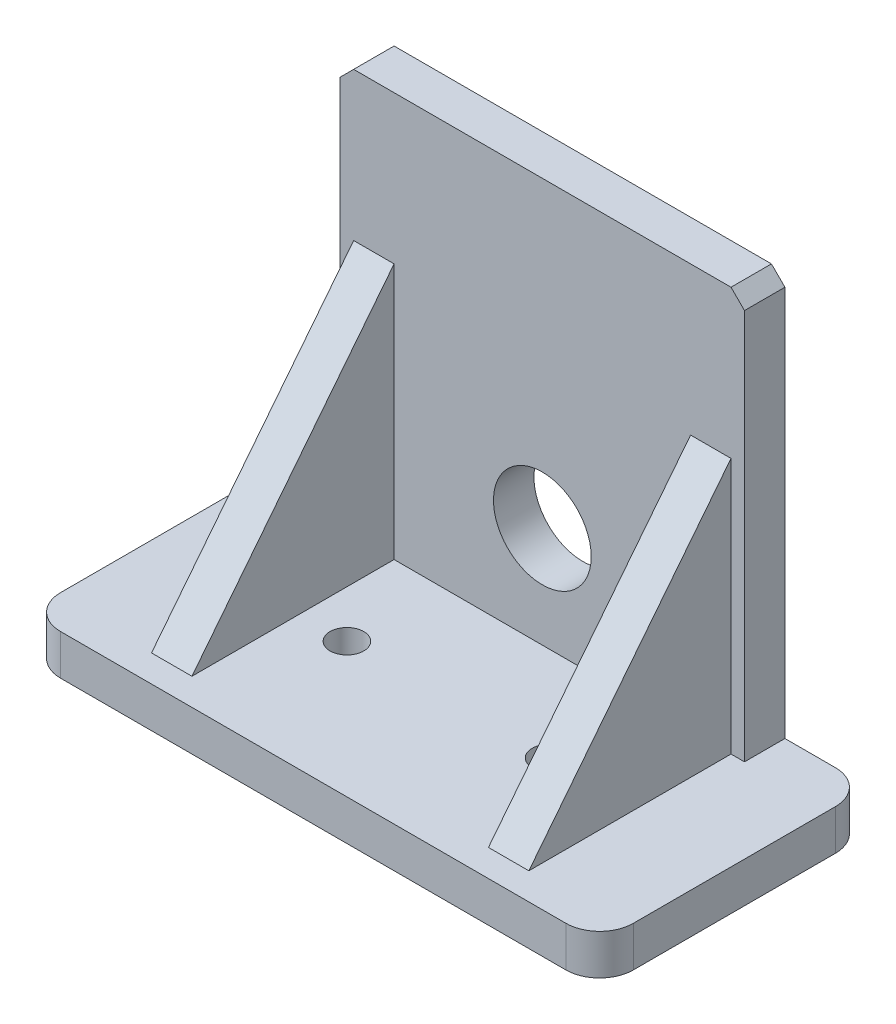
SolidWorks part; units mm, degrees
material "Alloy Steel"
ref_plane "Front Plane" through (0, 0, 0) normal (0, 0, 1) x (1, 0, 0)
ref_plane "Top Plane" through (0, 0, 0) normal (0, 1, 0) x (1, 0, 0)
ref_plane "Right Plane" through (0, 0, 0) normal (1, 0, 0) x (0, 0, -1)
sketch "Sketch1" plane through (0, 0, 0) normal (0, 1, 0) x (1, 0, 0)
  line L0 (0, 0) -> (-13873.7323, 0) construction
  line L1 (0, 0) -> (0, 13873.7323) construction
  line L3 (-37.5, -20) -> (37.5, -20)
  line L4 (-42.5, -15) -> (-42.5, 15)
  line L5 (-37.5, 20) -> (37.5, 20)
  line L6 (42.5, -15) -> (42.5, 15)
  line L7 (0, 20) -> (0, -20) construction
  line L8 (-42.5, 0) -> (42.5, 0) construction
  arc A2 (-37.5, -20) -> (-42.5, -15) centre (-37.5, -15) cw
  arc A3 (37.5, -20) -> (42.5, -15) centre (37.5, -15) ccw
  arc A4 (37.5, 20) -> (42.5, 15) centre (37.5, 15) cw
  arc A5 (-42.5, 15) -> (-37.5, 20) centre (-37.5, 15) cw
  circle A8 centre (-15, 0) radius 2.5
  circle A9 centre (15, 0) radius 2.5
  point P5 (0, 0)
  point P15 (-42.5, -20)
  point P18 (42.5, -20)
  point P24 (-42.5, 20)
  dimension "D3" = 5
  dimension "D4" = 5
  dimension "D5" = 30
  dimension "D6" = 15
  dimension "D7" = 5
  dimension "D1" = 40
  dimension "D2" = 85
extrude "Boss-Extrude1" add sketch "Sketch1" along normal blind 6
sketch "Sketch2" plane through (-42.5, 0, 0) normal (-1, 0, 0) x (0, 0, 1)
  line L0 (-20, 0) -> (-20, 50000) construction
  line L2 (-20, 6) -> (-14, 6)
  line L3 (-20, 6) -> (-20, 66)
  line L4 (-20, 66) -> (-14, 66)
  line L5 (-14, 6) -> (-14, 66)
  dimension "D1" = 60
  dimension "D2" = 6
extrude "Boss-Extrude2" add sketch "Sketch2" against normal blind 60 from offset 12.5 offset against normal yes
sketch "Sketch4" plane through (-30, 0, 0) normal (-1, 0, 0) x (0, 0, 1)
  line L0 (16, 6) -> (-14, 44)
  line L1 (-14, 6) -> (16, 6)
  line L2 (-14, 6) -> (-14, 44)
  dimension "D1" = 38
  dimension "D2" = 30
extrude "Boss-Extrude3" add sketch "Sketch4" against normal blind 6 from offset 2 offset against normal yes
sketch "Sketch5" plane through (30, 0, 0) normal (1, 0, 0) x (0, 0, -1)
  line L0 (-16, 6) -> (14, 44)
  line L1 (14, 6) -> (-16, 6)
  line L2 (14, 6) -> (14, 44)
  dimension "D1" = 38
  dimension "D2" = 30
extrude "Boss-Extrude4" add sketch "Sketch5" against normal blind 6 from offset 2 offset against normal yes
sketch "Sketch6" plane through (0, 0, -14) normal (0, 0, 1) x (1, 0, 0)
  line L0 (0, 0) -> (0, 50000) construction
  line L6 (0, 21) -> (0, 111) construction
  line L7 (30, 66) -> (-30, 66) construction
  circle A1 centre (0, 21) radius 7.25
  dimension "D2" = 45
  dimension "D1" = 14.5
extrude "Cut-Extrude1" cut sketch "Sketch6" against normal through all
chamfer "Chamfer3" distance 2 angle 45 2 edges at (30, 66, -17) (-30, 66, -17)
